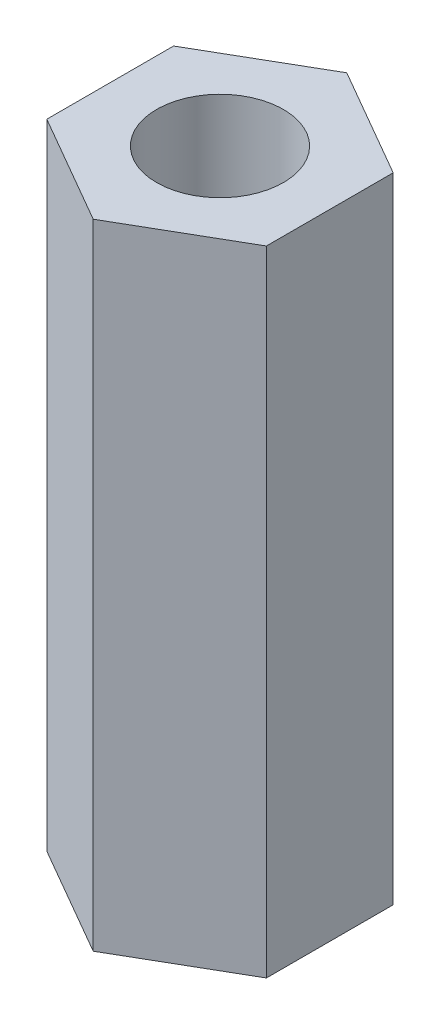
SolidWorks part; units mm, degrees
material "Brass"
ref_plane "Front Plane" through (0, 0, 0) normal (0, 0, 1) x (1, 0, 0)
ref_plane "Top Plane" through (0, 0, 0) normal (0, 1, 0) x (1, 0, 0)
ref_plane "Right Plane" through (0, 0, 0) normal (1, 0, 0) x (0, 0, -1)
sketch "Sketch1" plane through (0, 0, 0) normal (0, 1, 0) x (1, 0, 0)
  line L1 (0, 3) -> (-2.5981, 1.5)
  line L2 (-2.5981, 1.5) -> (-2.5981, -1.5)
  line L3 (-2.5981, -1.5) -> (0, -3)
  line L4 (0, -3) -> (2.5981, -1.5)
  line L5 (2.5981, -1.5) -> (2.5981, 1.5)
  line L6 (2.5981, 1.5) -> (0, 3)
  circle A0 centre (0, 0) radius 2.5981 construction
  circle A1 centre (0, 0) radius 1.5
  dimension "D2" = 3
  dimension "D1" = 6
extrude "Boss-Extrude1" add sketch "Sketch1" along normal blind 15
